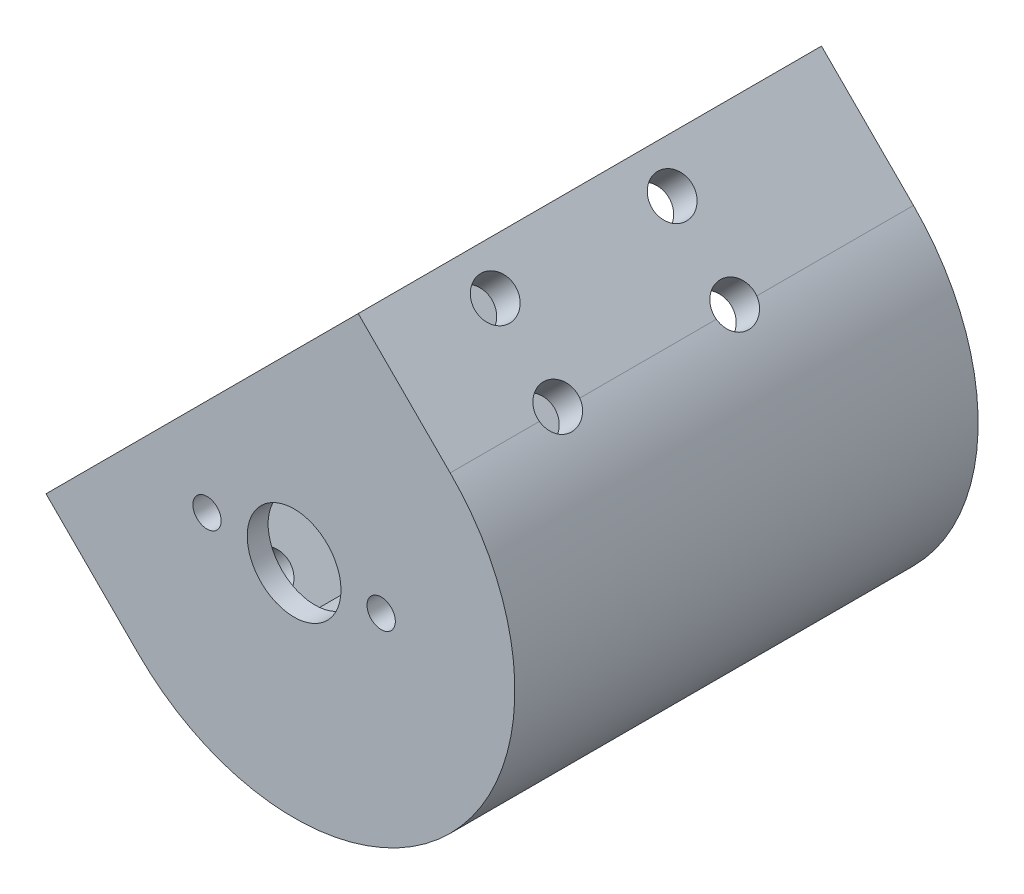
SolidWorks part; units mm, degrees
ref_plane "Front Plane" through (0, 0, 0) normal (0, 0, 1) x (1, 0, 0)
ref_plane "Top Plane" through (0, 0, 0) normal (0, 1, 0) x (1, 0, 0)
ref_plane "Right Plane" through (0, 0, 0) normal (1, 0, 0) x (0, 0, -1)
sketch "Sketch2" plane through (0, 0, 0) normal (0, 0, 1) x (1, 0, 0)
  line L0 (5.8322, 32.2441) -> (9.1998, 35.6117)
  line L1 (9.1998, 35.6117) -> (22.4057, 22.4057)
  line L2 (0, 0) -> (38.8156, 38.8156) construction
  line L3 (-32.2441, -5.8322) -> (-35.6117, -9.1998)
  line L4 (-35.6117, -9.1998) -> (-22.4057, -22.4057)
  line L5 (5.8322, 32.2441) -> (22.7151, 15.3612)
  line L6 (22.7151, 15.3612) -> (17.5669, 10.213)
  line L7 (22.7151, 15.3612) -> (20.47, 13.1161) construction
  line L8 (-32.2441, -5.8322) -> (-15.3612, -22.7151)
  line L9 (-15.3612, -22.7151) -> (-10.213, -17.5669)
  line L10 (-13.1161, -20.47) -> (-15.3612, -22.7151) construction
  arc A0 (-22.4057, -22.4057) -> (22.4057, 22.4057) centre (0, 0) ccw
  arc A1 (-10.213, -17.5669) -> (17.5669, 10.213) centre (0, 0) ccw
  dimension "D1" = 4.7625
  dimension "D3" = 40.64
  dimension "D2" = 4.7625
extrude "Boss-Extrude1" add sketch "Sketch2" against normal blind 63.5
sketch "Sketch4" plane through (0, 0, 0) normal (0, 0, 1) x (1, 0, 0)
  line L0 (9.1998, 35.6117) -> (-35.6117, -9.1998)
  line L1 (-35.6117, -9.1998) -> (-22.4057, -22.4057)
  line L2 (9.1998, 35.6117) -> (22.4057, 22.4057)
  arc A0 (-22.4057, -22.4057) -> (22.4057, 22.4057) centre (0, 0) ccw construction
  arc A1 (-22.4057, -22.4057) -> (22.4057, 22.4057) centre (0, 0) ccw
  circle A2 centre (0, 0) radius 6.731
  circle A3 centre (12.5, 0) radius 2.031
  circle A4 centre (-12.5, 0) radius 2.031
  dimension "D1" = 13.462
  dimension "D2" = 4.062
extrude "Boss-Extrude2" add sketch "Sketch4" along normal up to surface (3 mm away)
sketch "Sketch5" plane through (-22.4057, -22.4057, 0) normal (-0.7071, -0.7071, 0) x (0, 0, 1)
  circle A0 centre (-12.7, 0.3626) radius 2.921
  circle A4 centre (-12.7, 13.0626) radius 2.921
  circle A5 centre (-38.1, 13.0626) radius 2.921
  circle A6 centre (-38.1, 0.3626) radius 2.921
  dimension "D1" = 5.842
extrude "Cut-Extrude3" cut sketch "Sketch5" against normal through all
